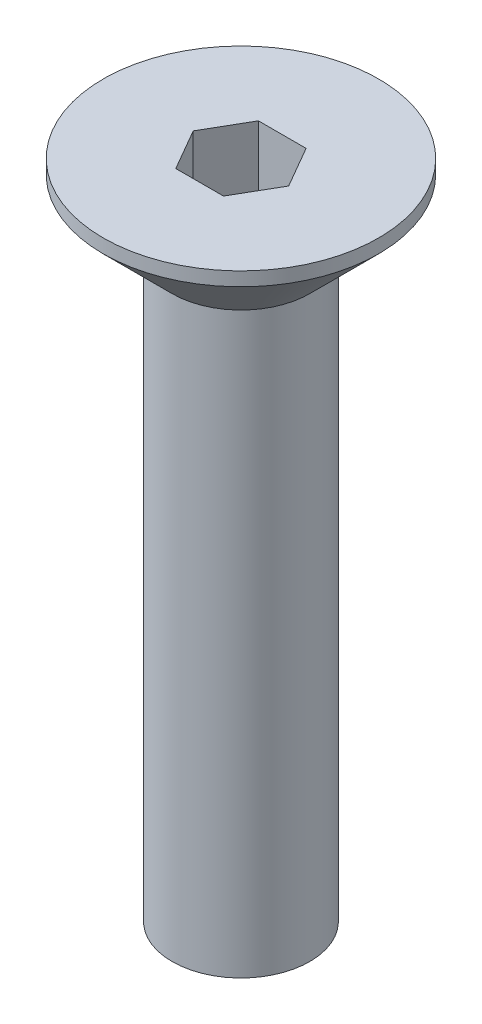
SolidWorks part; units mm, degrees
material "AISI 304"
ref_plane "Front Plane" through (0, 0, 0) normal (0, 0, 1) x (1, 0, 0)
ref_plane "Top Plane" through (0, 0, 0) normal (0, 1, 0) x (1, 0, 0)
ref_plane "Right Plane" through (0, 0, 0) normal (1, 0, 0) x (0, 0, -1)
sketch "Sketch1" plane through (0, 0, 0) normal (0, 0, 1) x (1, 0, 0)
  line L0 (0, 61.6916) -> (0, -59.3578) construction
  line L1 (0, -12) -> (1.25, -12)
  line L2 (1.25, -12) -> (1.25, -1.5)
  line L3 (-2.9885, 0.2385) -> (-1.25, -1.5) construction
  line L4 (2.5, 0) -> (2.5, -0.25)
  line L5 (2.5, 0) -> (0, 0)
  line L6 (0, 0) -> (0, -12)
  line L7 (1.25, -1.5) -> (2.5, -0.25)
  dimension "D1" = 90
  dimension "D2" = 5
  dimension "D3" = 2.5
  dimension "D4" = 1.5
  dimension "D5" = 12
  dimension "D6" = 0.25
revolve "Revolve1" add sketch "Sketch1" angle 360 about L0
sketch "Sketch2" plane through (0, 0, 0) normal (0, 1, 0) x (-1, 0, 0)
  line L1 (-0.433, -0.75) -> (0.433, -0.75)
  line L2 (0.433, -0.75) -> (0.866, 0)
  line L3 (0.866, 0) -> (0.433, 0.75)
  line L4 (0.433, 0.75) -> (-0.433, 0.75)
  line L5 (-0.433, 0.75) -> (-0.866, 0)
  line L6 (-0.866, 0) -> (-0.433, -0.75)
  circle A0 centre (0, 0) radius 0.75 construction
  dimension "D1" = 1.5
extrude "Cut-Extrude1" cut sketch "Sketch2" against normal blind 1.5
